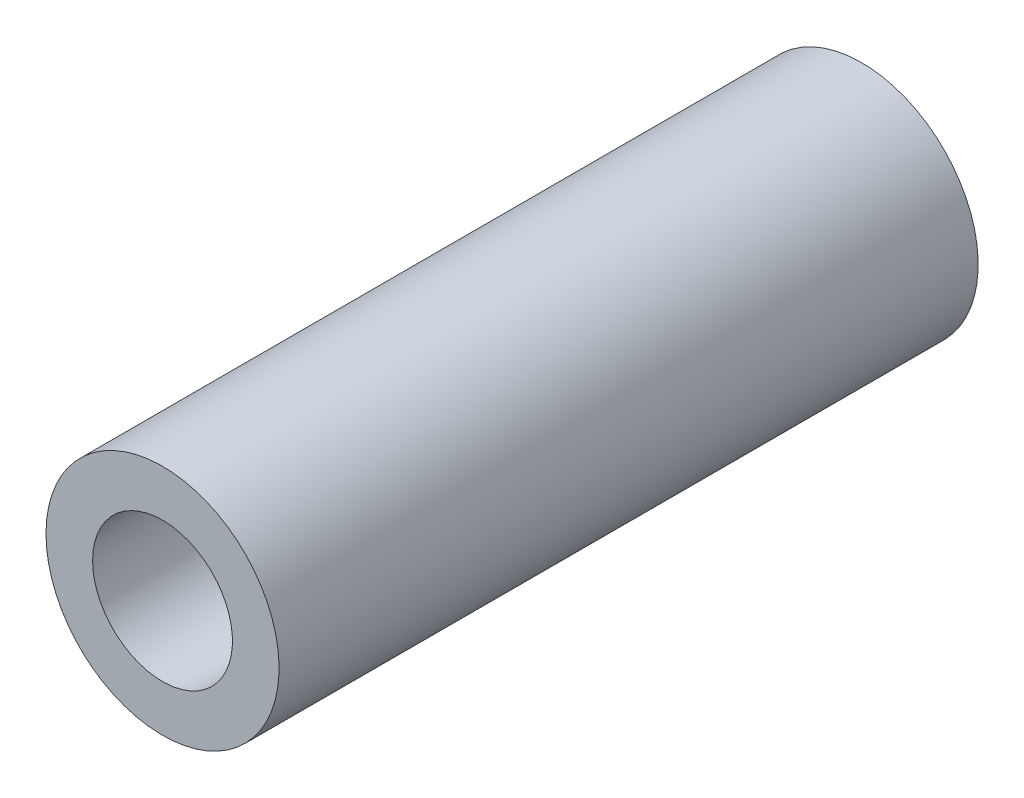
SolidWorks part; units mm, degrees
ref_plane "前视基准面" through (0, 0, 0) normal (0, 0, 1) x (1, 0, 0)
ref_plane "上视基准面" through (0, 0, 0) normal (0, 1, 0) x (1, 0, 0)
ref_plane "右视基准面" through (0, 0, 0) normal (1, 0, 0) x (0, 0, -1)
sketch "草图1" plane through (0, 0, 0) normal (0, 0, 1) x (1, 0, 0)
  circle A0 centre (0, 0) radius 4.5
  circle A1 centre (0, 0) radius 7.5
extrude "凸台-拉伸1" add sketch "草图1" along normal mid plane 45
